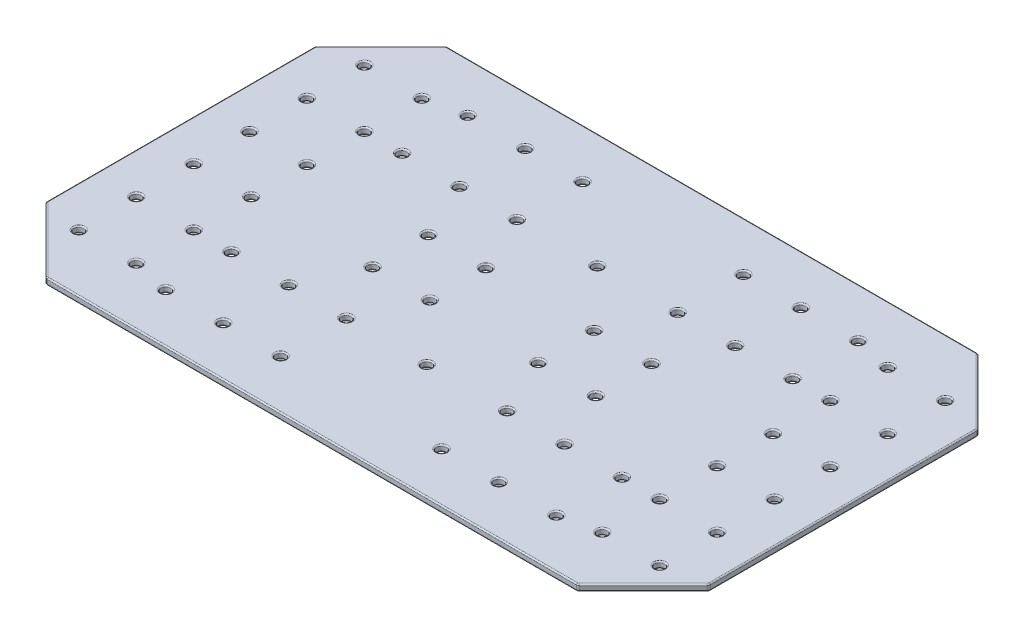
SolidWorks part; units mm, degrees
ref_plane "Front Plane" through (0, 0, 0) normal (0, 0, 1) x (1, 0, 0)
ref_plane "Top Plane" through (0, 0, 0) normal (0, 1, 0) x (1, 0, 0)
ref_plane "Right Plane" through (0, 0, 0) normal (1, 0, 0) x (0, 0, -1)
sketch "Sketch1" plane through (0, 0, 0) normal (0, 1, 0) x (1, 0, 0)
  line L1 (0, 0) -> (404, 0)
  line L2 (0, 0) -> (0, -244)
  line L3 (0, -244) -> (404, -244)
  line L4 (404, 0) -> (404, -244)
  circle A0 centre (118, -30) radius 3
  circle A1 centre (118, -214) radius 3
  circle A2 centre (286, -30) radius 3
  circle A3 centre (286, -214) radius 3
  circle A4 centre (118, -70) radius 3
  circle A5 centre (118, -174) radius 3
  circle A6 centre (286, -70) radius 3
  circle A7 centre (286, -174) radius 3
  circle A8 centre (321, -30) radius 3
  circle A9 centre (321, -70) radius 3
  circle A10 centre (321, -174) radius 3
  circle A12 centre (83, -214) radius 3
  circle A13 centre (83, -174) radius 3
  circle A14 centre (83, -70) radius 3
  circle A15 centre (83, -30) radius 3
  circle A16 centre (321, -214) radius 3
  dimension "D3" = 6
  dimension "D4" = 118
  dimension "D5" = 30
  dimension "D6" = 6
  dimension "D7" = 30
  dimension "D8" = 118
  dimension "D9" = 30
  dimension "D10" = 30
  dimension "D11" = 118
  dimension "D13" = 6
  dimension "D14" = 6
  dimension "D15" = 6
  dimension "D16" = 6
  dimension "D17" = 6
  dimension "D18" = 6
  dimension "D19" = 35
  dimension "D20" = 30
  dimension "D22" = 35
  dimension "D24" = 118
  dimension "D25" = 35
  dimension "D23" = 40
  dimension "D26" = 30
  dimension "D27" = 6
  dimension "D28" = 40
  dimension "D30" = 6
  dimension "D31" = 70
  dimension "D32" = 83
  dimension "D33" = 35
  dimension "D34" = 30
  dimension "D35" = 6
  dimension "D36" = 118
  dimension "D37" = 40
  dimension "D38" = 6
  dimension "D39" = 6
  dimension "D40" = 35
  dimension "D41" = 70
  dimension "D42" = 118
  dimension "D43" = 6
  dimension "D44" = 70
  dimension "D45" = 70
  dimension "D46" = 35
  dimension "D47" = 6
  dimension "D48" = 6
  dimension "D49" = 30
  dimension "D50" = 35
  dimension "D1" = 244
  dimension "D2" = 404
  dimension "D12" = 118
  dimension "D21" = 40
  dimension "D29" = 118
extrude "Boss-Extrude1" add sketch "Sketch1" along normal blind 4
sketch "Sketch2" plane through (0, 4, 0) normal (0, 1, 0) x (1, 0, 0)
  line L0 (404, 0) -> (0, 0) construction
  circle A0 centre (153, -30) radius 3
  circle A1 centre (153, -70) radius 3
  circle A2 centre (251, -30) radius 3
  circle A3 centre (118, -30) radius 3 construction
  circle A4 centre (118, -70) radius 3 construction
  circle A5 centre (286, -30) radius 3 construction
  circle A6 centre (251, -70) radius 3
  dimension "D2" = 35
  dimension "D3" = 6
  dimension "D4" = 6
  dimension "D5" = 35
  dimension "D6" = 70
  dimension "D7" = 6
  dimension "D8" = 30
  dimension "D9" = 35
  dimension "D10" = 6
  dimension "D1" = 30
extrude "Cut-Extrude1" cut sketch "Sketch2" against normal blind 4
sketch "Sketch3" plane through (0, 4, 0) normal (0, 1, 0) x (1, 0, 0)
  line L0 (0, -244) -> (404, -244) construction
  circle A0 centre (153, -174) radius 3
  circle A1 centre (153, -214) radius 3
  circle A2 centre (251, -174) radius 3
  circle A3 centre (251, -214) radius 3
  circle A4 centre (286, -174) radius 3 construction
  circle A5 centre (286, -214) radius 3 construction
  circle A6 centre (118, -174) radius 3 construction
  circle A7 centre (118, -214) radius 3 construction
  dimension "D1" = 6
  dimension "D2" = 6
  dimension "D3" = 6
  dimension "D4" = 6
  dimension "D5" = 70
  dimension "D6" = 35
  dimension "D7" = 35
  dimension "D8" = 40
  dimension "D9" = 0
  dimension "D11" = 0
  dimension "D12" = 0
  dimension "D10" = 35
extrude "Cut-Extrude2" cut sketch "Sketch3" against normal blind 4
sketch "Sketch4" plane through (0, 4, 0) normal (0, 1, 0) x (1, 0, 0)
  line L0 (40, 0) -> (0, -40)
  line L1 (404, 0) -> (0, 0) construction
  line L2 (0, 0) -> (0, -244) construction
  line L3 (0, -40) -> (-46.1258, -2.9925)
  line L4 (-46.1258, -2.9925) -> (13.9878, 26.0122)
  line L5 (13.9878, 26.0122) -> (40, 0)
  line L6 (0, -204) -> (40, -244)
  line L7 (0, -244) -> (404, -244) construction
  line L8 (40, -244) -> (24.7066, -266.6722)
  line L9 (24.7066, -266.6722) -> (-53.1609, -255.0272)
  line L10 (-53.1609, -255.0272) -> (-20.1801, -206.1337)
  line L11 (-20.1801, -206.1337) -> (0, -204)
  dimension "D1" = 40
  dimension "D2" = 40
  dimension "D3" = 40
  dimension "D4" = 40
extrude "Cut-Extrude3" cut sketch "Sketch4" against normal blind 10
sketch "Sketch5" plane through (0, 0, 0) normal (0, -1, 0) x (1, 0, 0)
  line L0 (364, 244) -> (404, 204)
  line L1 (40, 244) -> (404, 244) construction
  line L2 (404, 244) -> (404, 0) construction
  line L3 (404, 204) -> (459.2524, 174.0534)
  line L4 (459.2524, 174.0534) -> (447.7067, 59.4833)
  line L5 (447.7067, 59.4833) -> (404, 40)
  line L6 (404, 40) -> (364, 0)
  line L7 (404, 0) -> (40, 0) construction
  line L8 (364, 0) -> (446.9846, -16.1875)
  line L9 (446.9846, -16.1875) -> (481.2924, 67.7581)
  line L10 (481.2924, 67.7581) -> (498.4143, 241.0649)
  line L11 (498.4143, 241.0649) -> (405.4923, 260.9091)
  line L12 (405.4923, 260.9091) -> (364, 244)
  dimension "D1" = 40
  dimension "D2" = 40
  dimension "D3" = 40
  dimension "D4" = 40
extrude "Cut-Extrude4" cut sketch "Sketch5" against normal blind 10
sketch "Sketch6" plane through (0, 0, 0) normal (0, -1, 0) x (1, 0, 0)
  line L0 (364, 0) -> (40, 0) construction
  line L1 (0, 40) -> (0, 204) construction
  line L2 (40, 244) -> (364, 244) construction
  line L4 (404, 204) -> (404, 40) construction
  circle A0 centre (60, 209) radius 3
  circle A1 centre (60, 174) radius 3
  circle A2 centre (25, 174) radius 3
  circle A3 centre (25, 209) radius 3
  circle A4 centre (25, 70) radius 3
  circle A5 centre (60, 70) radius 3
  circle A6 centre (60, 35) radius 3
  circle A7 centre (25, 35) radius 3
  circle A9 centre (344, 209) radius 3
  circle A10 centre (379, 209) radius 3
  circle A11 centre (344, 174) radius 3
  circle A12 centre (379, 174) radius 3
  circle A13 centre (344, 70) radius 3
  circle A14 centre (379, 70) radius 3
  circle A15 centre (379, 35) radius 3
  circle A16 centre (344, 35) radius 3
  dimension "D1" = 6
  dimension "D2" = 6
  dimension "D3" = 6
  dimension "D4" = 6
  dimension "D5" = 6
  dimension "D6" = 6
  dimension "D7" = 6
  dimension "D8" = 6
  dimension "D9" = 35
  dimension "D10" = 35
  dimension "D11" = 35
  dimension "D12" = 25
  dimension "D13" = 25
  dimension "D14" = 35
  dimension "D15" = 35
  dimension "D16" = 35
  dimension "D17" = 25
  dimension "D18" = 25
  dimension "D19" = 35
  dimension "D21" = 35
  dimension "D23" = 35
  dimension "D25" = 6
  dimension "D26" = 6
  dimension "D27" = 6
  dimension "D28" = 6
  dimension "D29" = 6
  dimension "D30" = 6
  dimension "D31" = 6
  dimension "D32" = 6
  dimension "D34" = 35
  dimension "D35" = 25
  dimension "D36" = 35
  dimension "D37" = 35
  dimension "D38" = 60
  dimension "D39" = 35
  dimension "D40" = 35
  dimension "D41" = 35
  dimension "D42" = 35
  dimension "D43" = 60
  dimension "D44" = 25
  dimension "D45" = 35
  dimension "D46" = 25
  dimension "D47" = 35
  dimension "D48" = 35
  dimension "D20" = 35
  dimension "D22" = 35
  dimension "D24" = 35
  dimension "D33" = 35
extrude "Cut-Extrude5" cut sketch "Sketch6" against normal blind 10
sketch "Sketch7" plane through (0, 0, 0) normal (0, -1, 0) x (1, 0, 0)
  line L0 (0, 40) -> (0, 204) construction
  circle A0 centre (25, 139) radius 3
  circle A1 centre (60, 139) radius 3
  circle A2 centre (25, 105) radius 3
  circle A3 centre (60, 105) radius 3
  circle A4 centre (344, 139) radius 3
  circle A5 centre (379, 139) radius 3
  circle A6 centre (379, 105) radius 3
  circle A7 centre (344, 105) radius 3
  circle A8 centre (379, 174) radius 3 construction
  circle A9 centre (344, 174) radius 3 construction
  circle A10 centre (379, 70) radius 3 construction
  circle A11 centre (344, 70) radius 3 construction
  circle A12 centre (60, 174) radius 3 construction
  circle A13 centre (60, 70) radius 3 construction
  circle A14 centre (25, 70) radius 3 construction
  circle A15 centre (25, 174) radius 3 construction
  dimension "D1" = 6
  dimension "D2" = 6
  dimension "D3" = 6
  dimension "D4" = 6
  dimension "D5" = 6
  dimension "D6" = 6
  dimension "D7" = 6
  dimension "D8" = 6
  dimension "D9" = 0
  dimension "D10" = 0
  dimension "D11" = 35
  dimension "D12" = 35
  dimension "D13" = 0
  dimension "D14" = 35
  dimension "D15" = 0
  dimension "D16" = 35
  dimension "D18" = 35
  dimension "D19" = 35
  dimension "D20" = 35
  dimension "D21" = 25
  dimension "D22" = 25
  dimension "D24" = 35
  dimension "D17" = 35
  dimension "D23" = 35
extrude "Cut-Extrude6" cut sketch "Sketch7" against normal blind 10
sketch "Sketch8" plane through (0, 0, 0) normal (0, -1, 0) x (1, 0, 0)
  line L0 (40, 244) -> (364, 244) construction
  line L1 (364, 0) -> (40, 0) construction
  circle A0 centre (134, 139) radius 3
  circle A1 centre (169, 139) radius 3
  circle A2 centre (169, 105) radius 3
  circle A3 centre (134, 105) radius 3
  circle A4 centre (235, 139) radius 3
  circle A5 centre (270, 139) radius 3
  circle A6 centre (270, 105) radius 3
  circle A7 centre (235, 105) radius 3
  circle A8 centre (202, 174) radius 3
  circle A9 centre (202, 70) radius 3
  circle A11 centre (60, 139) radius 3 construction
  circle A12 centre (60, 105) radius 3 construction
  circle A13 centre (344, 139) radius 3 construction
  circle A14 centre (344, 105) radius 3 construction
  point P32 (202, 0)
  dimension "D1" = 6
  dimension "D2" = 6
  dimension "D3" = 6
  dimension "D4" = 6
  dimension "D5" = 6
  dimension "D6" = 6
  dimension "D7" = 6
  dimension "D8" = 6
  dimension "D9" = 6
  dimension "D10" = 6
  dimension "D11" = 0
  dimension "D12" = 0
  dimension "D13" = 0
  dimension "D14" = 0
  dimension "D15" = 35
  dimension "D16" = 35
  dimension "D17" = 74
  dimension "D18" = 74
  dimension "D19" = 35
  dimension "D20" = 35
  dimension "D21" = 0
  dimension "D22" = 0
  dimension "D23" = 0
  dimension "D24" = 74
  dimension "D26" = 34
  dimension "D27" = 70
  dimension "D28" = 70
  dimension "D29" = 0
  dimension "D30" = 0
  dimension "D25" = 74
extrude "Cut-Extrude7" cut sketch "Sketch8" against normal blind 10
fillet "Fillet3" radius 2 1 edges at (0, 2, 204)
fillet "Fillet4" radius 2 1 edges at (40, 2, 244)
fillet "Fillet5" radius 2 1 edges at (0, 2, 40)
fillet "Fillet6" radius 2 1 edges at (40, 2, 0)
fillet "Fillet7" radius 2 1 edges at (364, 2, 0)
fillet "Fillet8" radius 2 1 edges at (404, 2, 40)
fillet "Fillet9" radius 2 1 edges at (364, 2, 244)
fillet "Fillet10" radius 2 1 edges at (404, 2, 204)
fillet "Fillet11" radius 0.8 74 edges at (83, 0, 33) (83, 0, 73) (83, 0, 177) (83, 0, 217) (321, 0, 217) (321, 0, 177) (321, 0, 73) (321, 0, 33) (286, 0, 177) (286, 0, 73) (118, 0, 177) (118, 0, 73) (286, 0, 217) (286, 0, 33) (118, 0, 217) (118, 0, 33) (403.8478, 0, 40.0631) (384, 0, 20) (363.9369, 0, 0.1522) (202, 0, 0) (40.0631, 0, 0.1522) (20, 0, 20) (0.1522, 0, 40.0631) (0, 0, 122) (0.1522, 0, 203.9369) (20, 0, 224) (40.0631, 0, 243.8478) (202, 0, 244) (363.9369, 0, 243.8478) (384, 0, 224) (403.8478, 0, 203.9369) (404, 0, 122) (153, 0, 33) (251, 0, 73) (251, 0, 33) (153, 0, 73) (153, 0, 177) (251, 0, 217) (251, 0, 177) (153, 0, 217) (60, 0, 206) (344, 0, 67) (379, 0, 171) (344, 0, 171) (379, 0, 206) (379, 0, 67) (379, 0, 32) (344, 0, 32) (25, 0, 67) (25, 0, 206) (25, 0, 171) (60, 0, 171) (344, 0, 206) (25, 0, 32) (60, 0, 32) (60, 0, 67) (25, 0, 136) (344, 0, 102) (379, 0, 102) (379, 0, 136) (60, 0, 136) (25, 0, 102) (60, 0, 102) (344, 0, 136) (134, 0, 136) (202, 0, 171) (235, 0, 102) (270, 0, 102) (270, 0, 136) (169, 0, 136) (169, 0, 102) (134, 0, 102) (235, 0, 136) (202, 0, 67)
fillet "Fillet12" radius 0.8 74 edges at (83, 4, 33) (83, 4, 177) (321, 4, 217) (321, 4, 73) (286, 4, 177) (118, 4, 177) (286, 4, 217) (118, 4, 217) (118, 4, 33) (286, 4, 33) (118, 4, 73) (286, 4, 73) (321, 4, 33) (321, 4, 177) (83, 4, 217) (83, 4, 73) (153, 4, 33) (251, 4, 73) (251, 4, 33) (153, 4, 73) (153, 4, 177) (251, 4, 217) (251, 4, 177) (153, 4, 217) (363.9369, 4, 243.8478) (202, 4, 244) (40.0631, 4, 243.8478) (20, 4, 224) (0.1522, 4, 203.9369) (0, 4, 122) (0.1522, 4, 40.0631) (20, 4, 20) (40.0631, 4, 0.1522) (202, 4, 0) (363.9369, 4, 0.1522) (384, 4, 20) (403.8478, 4, 40.0631) (404, 4, 122) (403.8478, 4, 203.9369) (384, 4, 224) (60, 4, 212) (344, 4, 73) (379, 4, 177) (344, 4, 177) (379, 4, 212) (379, 4, 73) (379, 4, 38) (344, 4, 38) (25, 4, 73) (25, 4, 212) (25, 4, 177) (60, 4, 177) (344, 4, 212) (25, 4, 38) (60, 4, 38) (60, 4, 73) (25, 4, 142) (344, 4, 108) (379, 4, 108) (379, 4, 142) (60, 4, 142) (25, 4, 108) (60, 4, 108) (344, 4, 142) (134, 4, 142) (202, 4, 177) (235, 4, 108) (270, 4, 108) (270, 4, 142) (169, 4, 142) (169, 4, 108) (134, 4, 108) (235, 4, 142) (202, 4, 73)
